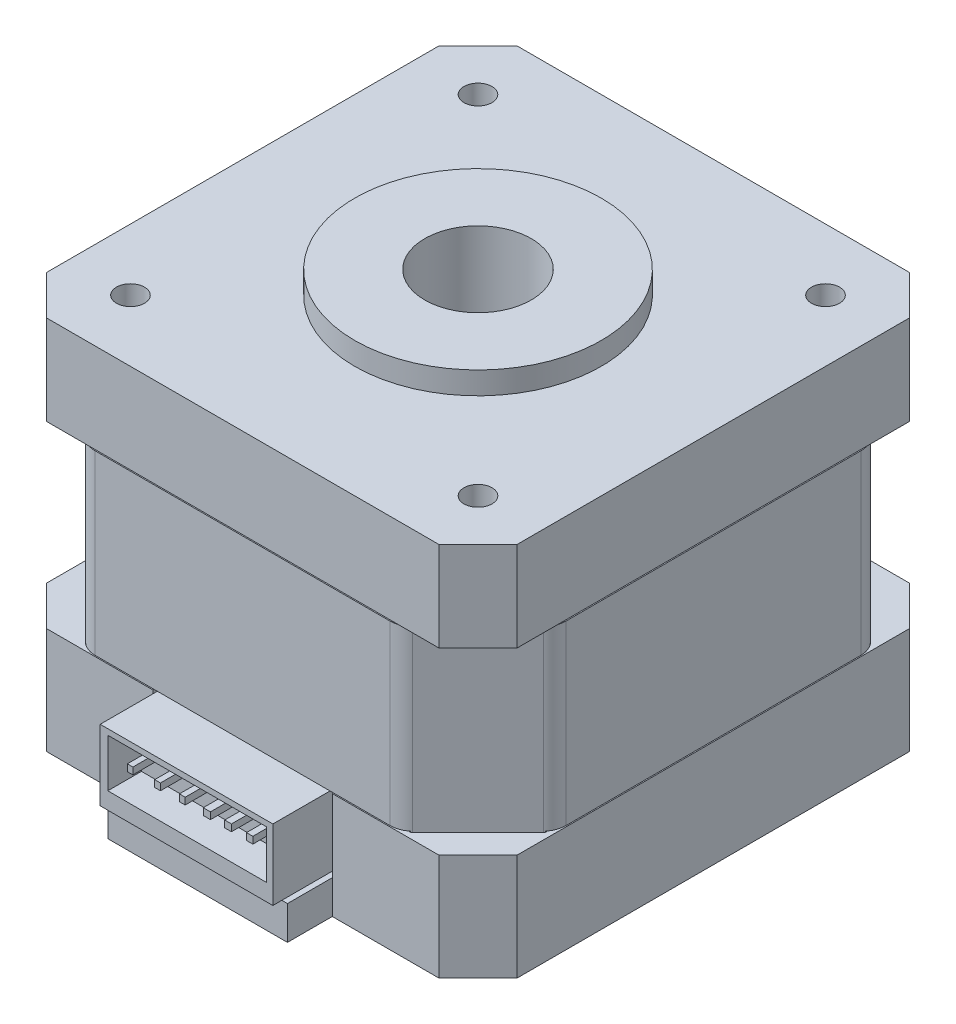
SolidWorks part; units mm, degrees
ref_plane "前视基准面" through (0, 0, 0) normal (0, 0, 1) x (1, 0, 0)
ref_plane "上视基准面" through (0, 0, 0) normal (0, 1, 0) x (1, 0, 0)
ref_plane "右视基准面" through (0, 0, 0) normal (1, 0, 0) x (0, 0, -1)
other "Configuration Table"
sketch "草图1" plane through (0, 0, 0) normal (0, 1, 0) x (1, 0, 0)
  line L0 (-21, 17.5) -> (-17.5, 21)
  line L1 (-17.5, 21) -> (17.5, 21)
  line L2 (-21, 17.5) -> (-21, -17.5)
  line L3 (-17.5, -21) -> (17.5, -21)
  line L4 (21, 17.5) -> (21, -17.5)
  line L5 (-21, 21) -> (21, -21) construction
  line L6 (-21, -21) -> (21, 21) construction
  line L7 (17.5, 21) -> (21, 17.5)
  line L8 (17.5, -21) -> (21, -17.5)
  line L9 (-21, -17.5) -> (-17.5, -21)
  line L11 (-15.5, 15.5) -> (15.5, 15.5) construction
  line L12 (-15.5, 15.5) -> (-15.5, -15.5) construction
  line L13 (-15.5, -15.5) -> (15.5, -15.5) construction
  line L14 (15.5, 15.5) -> (15.5, -15.5) construction
  line L15 (-15.5, 15.5) -> (15.5, -15.5) construction
  line L16 (-15.5, -15.5) -> (15.5, 15.5) construction
  circle A0 centre (-15.5, 15.5) radius 0.5
  circle A1 centre (15.5, 15.5) radius 0.5
  circle A2 centre (15.5, -15.5) radius 0.5
  circle A3 centre (-15.5, -15.5) radius 0.5
  point P0 (0, 0)
  point P14 (0, 0)
  dimension "D5" = 1
  dimension "D6" = 1
  dimension "D7" = 1
  dimension "D8" = 1
  dimension "D1" = 42
  dimension "D2" = 42
  dimension "D3" = 31
  dimension "D4" = 31
extrude "凸台-拉伸1" add sketch "草图1" along normal blind 8
sketch "草图2" plane through (0, 0, 0) normal (0, -1, 0) x (1, 0, 0)
  line L0 (-20.4142, 14.5858) -> (-14.5858, 20.4142)
  line L1 (-13.1716, 21) -> (13.1716, 21)
  line L2 (-21, 13.1716) -> (-21, -13.1716)
  line L3 (-13.1716, -21) -> (13.1716, -21)
  line L4 (21, 13.1716) -> (21, -13.1716)
  line L5 (-21, 21) -> (21, -21) construction
  line L6 (-21, -21) -> (21, 21) construction
  line L7 (14.5858, 20.4142) -> (20.4142, 14.5858)
  line L8 (14.5858, -20.4142) -> (20.4142, -14.5858)
  line L9 (-20.4142, -14.5858) -> (-14.5858, -20.4142)
  arc A0 (-20.4142, -14.5858) -> (-21, -13.1716) centre (-19, -13.1716) cw
  arc A1 (-14.5858, -20.4142) -> (-13.1716, -21) centre (-13.1716, -19) ccw
  arc A2 (14.5858, -20.4142) -> (13.1716, -21) centre (13.1716, -19) cw
  arc A3 (20.4142, -14.5858) -> (21, -13.1716) centre (19, -13.1716) ccw
  arc A4 (20.4142, 14.5858) -> (21, 13.1716) centre (19, 13.1716) cw
  arc A5 (14.5858, 20.4142) -> (13.1716, 21) centre (13.1716, 19) ccw
  arc A6 (-20.4142, 14.5858) -> (-21, 13.1716) centre (-19, 13.1716) ccw
  arc A7 (-14.5858, 20.4142) -> (-13.1716, 21) centre (-13.1716, 19) cw
  point P0 (0, 0)
  point P16 (-21, -14)
  point P19 (-14, -21)
  point P22 (14, -21)
  point P25 (21, -14)
  point P28 (21, 14)
  point P31 (14, 21)
  point P34 (-21, 14)
  point P37 (-14, 21)
  dimension "D2" = 2
extrude "凸台-拉伸2" add sketch "草图2" along normal blind 16
sketch "草图3" plane through (0, -16, 0) normal (0, -1, 0) x (1, 0, 0)
  line L0 (-21, 17.5) -> (-17.5, 21)
  line L1 (-17.5, 21) -> (17.5, 21)
  line L2 (-21, 17.5) -> (-21, -17.5)
  line L3 (-17.5, -21) -> (17.5, -21)
  line L4 (21, 17.5) -> (21, -17.5)
  line L5 (-21, 21) -> (21, -21) construction
  line L6 (-21, -21) -> (21, 21) construction
  line L7 (17.5, 21) -> (21, 17.5)
  line L8 (17.5, -21) -> (21, -17.5)
  line L9 (-21, -17.5) -> (-17.5, -21)
  line L11 (-15.5, 15.5) -> (15.5, 15.5) construction
  line L12 (-15.5, 15.5) -> (-15.5, -15.5) construction
  line L13 (-15.5, -15.5) -> (15.5, -15.5) construction
  line L14 (15.5, 15.5) -> (15.5, -15.5) construction
  line L15 (-15.5, 15.5) -> (15.5, -15.5) construction
  line L16 (-15.5, -15.5) -> (15.5, 15.5) construction
  point P0 (0, 0)
  point P14 (0, 0)
  dimension "D2" = 31
  dimension "D3" = 31
extrude "凸台-拉伸3" add sketch "草图3" along normal blind 9.5
sketch "草图5" plane through (0, 0, 0) normal (0, -1, 0) x (1, 0, 0)
  line L1 (-20.5, -20.5) -> (20.5, -20.5)
  line L2 (-20.5, -20.5) -> (-20.5, 20.5)
  line L3 (-20.5, 20.5) -> (20.5, 20.5)
  line L4 (20.5, -20.5) -> (20.5, 20.5)
  line L5 (-20.5, -20.5) -> (20.5, 20.5) construction
  line L6 (-20.5, 20.5) -> (20.5, -20.5) construction
  line L7 (-28.827, -28.1836) -> (28.827, -28.1836)
  line L8 (-28.827, -28.1836) -> (-28.827, 28.1836)
  line L9 (-28.827, 28.1836) -> (28.827, 28.1836)
  line L10 (28.827, -28.1836) -> (28.827, 28.1836)
  line L11 (-28.827, -28.1836) -> (28.827, 28.1836) construction
  line L12 (-28.827, 28.1836) -> (28.827, -28.1836) construction
  point P0 (0, 0)
  point P6 (0, 0)
  dimension "D1" = 41
  dimension "D2" = 41
extrude "切除-拉伸1" cut sketch "草图5" along normal blind 0.1
sketch "草图6" plane through (0, -16, 0) normal (0, 1, 0) x (1, 0, 0)
  line L1 (-20.5, 20.5) -> (20.5, 20.5)
  line L2 (-20.5, 20.5) -> (-20.5, -20.5)
  line L3 (-20.5, -20.5) -> (20.5, -20.5)
  line L4 (20.5, 20.5) -> (20.5, -20.5)
  line L5 (-20.5, 20.5) -> (20.5, -20.5) construction
  line L6 (-20.5, -20.5) -> (20.5, 20.5) construction
  line L7 (-29.4934, 28.4696) -> (29.4934, 28.4696)
  line L8 (-29.4934, 28.4696) -> (-29.4934, -28.4696)
  line L9 (-29.4934, -28.4696) -> (29.4934, -28.4696)
  line L10 (29.4934, 28.4696) -> (29.4934, -28.4696)
  line L11 (-29.4934, 28.4696) -> (29.4934, -28.4696) construction
  line L12 (-29.4934, -28.4696) -> (29.4934, 28.4696) construction
  point P0 (0, 0)
  point P6 (0, 0)
  dimension "D1" = 41
  dimension "D2" = 41
extrude "切除-拉伸2" cut sketch "草图6" along normal blind 0.1
sketch "草图7" plane through (0, -25.5, 0) normal (0, -1, 0) x (1, 0, 0)
  line L1 (-15.5, 15.5) -> (15.5, 15.5) construction
  line L2 (-15.5, 15.5) -> (-15.5, -15.5) construction
  line L3 (-15.5, -15.5) -> (15.5, -15.5) construction
  line L4 (15.5, 15.5) -> (15.5, -15.5) construction
  line L5 (-15.5, 15.5) -> (15.5, -15.5) construction
  line L6 (-15.5, -15.5) -> (15.5, 15.5) construction
  circle A0 centre (-15.5, 15.5) radius 3
  circle A1 centre (15.5, 15.5) radius 3
  circle A2 centre (-15.5, -15.5) radius 3
  circle A3 centre (15.5, -15.5) radius 3
  point P0 (0, 0)
  dimension "D3" = 6
  dimension "D4" = 6
  dimension "D5" = 6
  dimension "D6" = 6
  dimension "D1" = 31
  dimension "D2" = 31
extrude "切除-拉伸3" cut sketch "草图7" against normal blind 3
hole_wizard "M3 螺纹孔的螺纹孔钻头1" positions "草图8" profile "草图9" hole size "M3" standard "GB"
sketch "草图8" plane through (0, 8, 0) normal (0, 1, 0) x (1, 0, 0)
  point P0 (-15.5, 15.5)
  point P3 (15.5, 15.5)
  point P6 (-15.5, -15.5)
  point P9 (15.5, -15.5)
sketch "草图9" plane through (-15.5, 8, -15.5) normal (1, 0, 0) x (0, 0, 1)
  line L0 (0, 0) -> (0, 5.7511)
  line L1 (0, 5.7511) -> (1.25, 5)
  line L2 (1.25, 5) -> (1.25, 0)
  line L5 (1.25, 0) -> (0, 0)
  line L10 (0, 5.7511) -> (-1.25, 5) construction
  line L11 (0, -6.35) -> (0, 107.95) construction
  dimension "孔直径" = 2.5
  dimension "孔深度" = 5
  dimension "导头角度" = 118
cosmetic thread "装饰螺纹线1" parameters "D2"=3
cosmetic thread "装饰螺纹线2" parameters "D2"=3
cosmetic thread "装饰螺纹线3" parameters "D2"=3
cosmetic thread "装饰螺纹线4" parameters "D2"=3
sketch "草图10" plane through (0, 8, 0) normal (0, 1, 0) x (1, 0, 0)
  circle A0 centre (0, 0) radius 11
  dimension "D1" = 22
extrude "凸台-拉伸4" add sketch "草图10" along normal blind 2
sketch "草图11" plane through (0, 10, 0) normal (0, 1, 0) x (1, 0, 0)
  circle A0 centre (0, 0) radius 4.75
  dimension "D1" = 9.5
extrude "切除-拉伸4" cut sketch "草图11" against normal blind 69
sketch "草图12" plane through (0, -25.5, 0) normal (0, -1, 0) x (1, 0, 0)
  circle A0 centre (0, 0) radius 5
  dimension "D1" = 10
extrude "切除-拉伸5" cut sketch "草图12" against normal blind 3
sketch "草图13" plane through (0, -25.5, 0) normal (0, -1, 0) x (1, 0, 0)
  text T0 "17HS3401"
extrude "切除-拉伸6" cut sketch "草图13" against normal blind 0.1
sketch "草图14" plane through (0, -25.5, 0) normal (0, -1, 0) x (1, 0, 0)
  line L0 (0, 0) -> (0, 35.3353) construction
  line L1 (17.5, 21) -> (-17.5, 21) construction
  line L2 (-8, 21) -> (8, 21)
  line L3 (-8, 21) -> (-8, 25)
  line L4 (-8, 25) -> (8, 25)
  line L5 (8, 21) -> (8, 25)
  dimension "D1" = 16
  dimension "D2" = 8
  dimension "D3" = 4
extrude "凸台-拉伸5" add sketch "草图14" against normal blind 3
sketch "草图15" plane through (0, 0, 21) normal (0, 0, 1) x (1, 0, 0)
  line L0 (17.5, -16) -> (-17.5, -16) construction
  line L1 (-8, -22.5) -> (8, -22.5)
  line L2 (-8, -22.5) -> (-8, -16)
  line L3 (-8, -16) -> (8, -16)
  line L4 (8, -22.5) -> (8, -16)
extrude "切除-拉伸7" cut sketch "草图15" against normal blind 1
sketch "草图16" plane through (0, 0, 20) normal (0, 0, 1) x (1, 0, 0)
  line L0 (8, -16) -> (-8, -16) construction
  line L1 (-7.7, -16) -> (7.7, -16)
  line L2 (-7.7, -16) -> (-7.7, -22.3)
  line L3 (-7.7, -22.3) -> (7.7, -22.3)
  line L4 (7.7, -16) -> (7.7, -22.3)
  line L5 (-8, -16) -> (-8, -22.5) construction
  line L6 (8, -22.5) -> (8, -16) construction
  line L7 (8, -22.5) -> (-8, -22.5) construction
  dimension "D1" = 0.3
  dimension "D2" = 0.3
  dimension "D3" = 0.2
extrude "凸台-拉伸6" add sketch "草图16" along normal blind 6
sketch "草图17" plane through (0, 0, 26) normal (0, 0, 1) x (1, 0, 0)
  line L1 (-7.0246, -16.5051) -> (7.1457, -16.5051)
  line L2 (-7.0246, -16.5051) -> (-7.0246, -20.8002)
  line L3 (-7.0246, -20.8002) -> (7.1457, -20.8002)
  line L4 (7.1457, -16.5051) -> (7.1457, -20.8002)
  line L5 (-5.2808, -17.845) -> (-4.7852, -17.845)
  line L6 (-5.2808, -17.845) -> (-5.2808, -18.4507)
  line L7 (-5.2808, -18.4507) -> (-4.7852, -18.4507)
  line L8 (-4.7852, -17.845) -> (-4.7852, -18.4507)
  line L9 (-2.8396, -17.845) -> (-2.3256, -17.845)
  line L10 (-2.8396, -17.845) -> (-2.8396, -18.4507)
  line L11 (-2.8396, -18.4507) -> (-2.3256, -18.4507)
  line L12 (-2.3256, -17.845) -> (-2.3256, -18.4507)
  line L13 (-0.6369, -17.845) -> (-0.123, -17.845)
  line L14 (-0.6369, -17.845) -> (-0.6369, -18.4507)
  line L15 (-0.6369, -18.4507) -> (-0.123, -18.4507)
  line L16 (-0.123, -17.845) -> (-0.123, -18.4507)
  line L17 (1.4923, -17.845) -> (2.1347, -17.845)
  line L18 (1.4923, -17.845) -> (1.4923, -18.4507)
  line L19 (1.4923, -18.4507) -> (2.1347, -18.4507)
  line L20 (2.1347, -17.845) -> (2.1347, -18.4507)
  line L21 (3.4012, -17.845) -> (4.007, -17.845)
  line L22 (3.4012, -17.845) -> (3.4012, -18.4507)
  line L23 (3.4012, -18.4507) -> (4.007, -18.4507)
  line L24 (4.007, -17.845) -> (4.007, -18.4507)
  line L25 (5.3469, -17.845) -> (5.9159, -17.845)
  line L26 (5.3469, -17.845) -> (5.3469, -18.4507)
  line L27 (5.3469, -18.4507) -> (5.9159, -18.4507)
  line L28 (5.9159, -17.845) -> (5.9159, -18.4507)
extrude "切除-拉伸8" cut sketch "草图17" against normal blind 3
